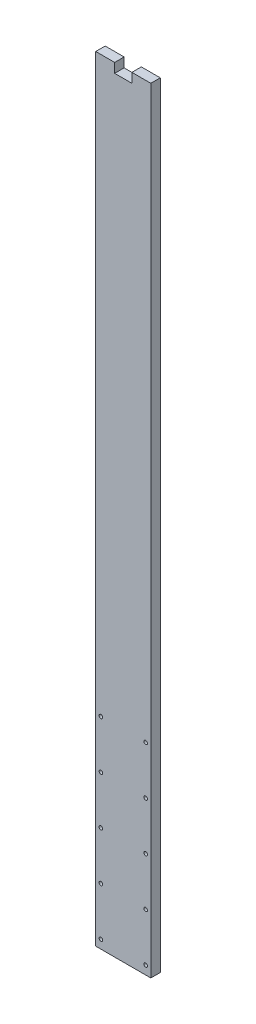
SolidWorks part; units mm, degrees
material "ﾁｰｸ材"
ref_plane "正面" through (0, 0, 0) normal (0, 0, 1) x (1, 0, 0)
ref_plane "平面" through (0, 0, 0) normal (0, 1, 0) x (1, 0, 0)
ref_plane "右側面" through (0, 0, 0) normal (1, 0, 0) x (0, 0, -1)
sketch "ｽｹｯﾁ1" plane through (0, 0, 0) normal (0, 0, 1) x (1, 0, 0)
  line L1 (0, 0) -> (32, 0)
  line L2 (0, 0) -> (0, 450)
  line L3 (0, 450) -> (32, 450)
  line L4 (32, 0) -> (32, 450)
  dimension "D1" = 32
  dimension "D2" = 450
extrude "ﾎﾞｽ - 押し出し1" add sketch "ｽｹｯﾁ1" along normal blind 5.5
sketch "ｽｹｯﾁ2" plane through (0, 0, 5.5) normal (0, 0, 1) x (1, 0, 0)
  line L0 (32, 450) -> (0, 450) construction
  line L1 (11, 444.5) -> (21, 444.5)
  line L2 (11, 444.5) -> (11, 450)
  line L3 (11, 450) -> (21, 450)
  line L4 (21, 444.5) -> (21, 450)
  line L5 (11, 444.5) -> (21, 450) construction
  line L6 (11, 450) -> (21, 444.5) construction
  line L7 (0, 450) -> (0, 0) construction
  point P0 (16, 447.25)
  point P7 (16, 450)
  point P8 (10.1151, 447.25)
  dimension "D1" = 10
  dimension "D2" = 5.5
  dimension "D3" = 16
extrude "ｶｯﾄ - 押し出し1" cut sketch "ｽｹｯﾁ2" against normal blind 5.5
sketch "ｽｹｯﾁ3" plane through (0, 0, 5.5) normal (0, 0, 1) x (1, 0, 0)
  line L0 (0, 0) -> (32, 0) construction
  line L1 (3, 5) -> (3, 33) construction
  circle A0 centre (3, 5) radius 1.05
  circle A1 centre (29, 5) radius 1.05
  circle A2 centre (3, 33) radius 1.05
  circle A3 centre (29, 33) radius 1.05
  circle A4 centre (3, 61) radius 1.05
  circle A5 centre (29, 61) radius 1.05
  circle A6 centre (3, 89) radius 1.05
  circle A7 centre (29, 89) radius 1.05
  circle A8 centre (3, 117) radius 1.05
  circle A9 centre (29, 117) radius 1.05
  point P6 (16, 0)
  dimension "D1" = 2.1
  dimension "D2" = 13
  dimension "D3" = 13
  dimension "D4" = 5
  dimension "D6" = 28
  dimension "D5" = 5
extrude "ｶｯﾄ - 押し出し2" cut sketch "ｽｹｯﾁ3" against normal blind 10
